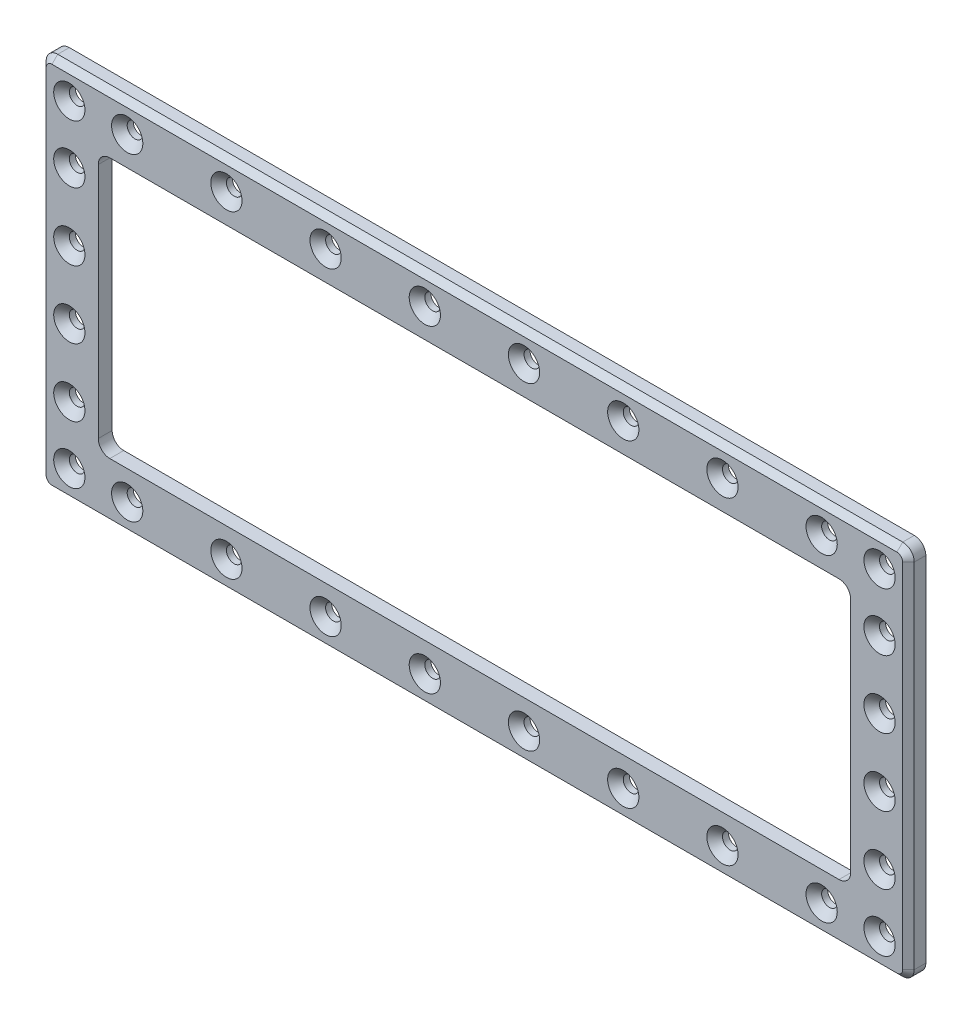
SolidWorks part; units mm, degrees
material "AISI Type 316L stainless steel"
ref_plane "Front Plane" through (0, 0, 0) normal (0, 0, 1) x (1, 0, 0)
ref_plane "Top Plane" through (0, 0, 0) normal (0, 1, 0) x (1, 0, 0)
ref_plane "Right Plane" through (0, 0, 0) normal (1, 0, 0) x (0, 0, -1)
sketch "Sketch1" plane through (0, 0, 0) normal (0, 0, 1) x (1, 0, 0)
  line L1 (75, -32.5) -> (-75, -32.5)
  line L2 (75, -32.5) -> (75, 32.5)
  line L3 (75, 32.5) -> (-75, 32.5)
  line L4 (-75, -32.5) -> (-75, 32.5)
  line L5 (75, -32.5) -> (-75, 32.5) construction
  line L6 (75, 32.5) -> (-75, -32.5) construction
  dimension "D1" = 150
  dimension "D2" = 65
extrude "Boss-Extrude1" add sketch "Sketch1" along normal blind 3
sketch "Sketch2" plane through (0, 0, 3) normal (0, 0, 1) x (1, 0, 0)
  line L1 (65, -22.5) -> (-65, -22.5)
  line L2 (65, -22.5) -> (65, 22.5)
  line L3 (65, 22.5) -> (-65, 22.5)
  line L4 (-65, -22.5) -> (-65, 22.5)
  line L5 (65, -22.5) -> (-65, 22.5) construction
  line L6 (65, 22.5) -> (-65, -22.5) construction
  point P0 (0, 0)
  dimension "D1" = 45
  dimension "D2" = 130
extrude "Cut-Extrude1" cut sketch "Sketch2" against normal through all
fillet "Fillet1" radius 2 8 edges at (75, 32.5, 1.5) (75, -32.5, 1.5) (-75, -32.5, 1.5) (-75, 32.5, 1.5) (65, 22.5, 1.5) (65, -22.5, 1.5) (-65, -22.5, 1.5) (-65, 22.5, 1.5)
sketch "Sketch3" plane through (0, 0, 0) normal (0, 0, 1) x (1, 0, 0)
  line L1 (72.5, -30) -> (-72.5, -30)
  line L2 (72.5, -30) -> (72.5, 30)
  line L3 (72.5, 30) -> (-72.5, 30)
  line L4 (-72.5, -30) -> (-72.5, 30)
  line L5 (72.5, -30) -> (-72.5, 30) construction
  line L6 (72.5, 30) -> (-72.5, -30) construction
  point P0 (0, 0)
  dimension "D1" = 60
  dimension "D2" = 145
extrude "Cut-Extrude2" cut sketch "Sketch3" along normal blind 0.6
fillet "Fillet2" radius 2 4 edges at (-72.5, -30, 0.3) (72.5, -30, 0.3) (72.5, 30, 0.3) (-72.5, 30, 0.3)
sketch "Sketch4" plane through (0, 0, 3) normal (0, 0, 1) x (1, 0, 0)
  line L0 (-75, 30.5) -> (-75, -30.5) construction
  line L1 (73, 32.5) -> (-73, 32.5) construction
  line L2 (0, -1.65) -> (0, 1.65) construction
  line L3 (1.65, 0) -> (-1.65, 0) construction
  point P0 (-70, 27.5)
  point P1 (-60, 27.5)
  point P2 (-70, 17.5)
  point P7 (-42.8571, 27.5)
  point P8 (-25.7143, 27.5)
  point P9 (70, -17.5)
  point P10 (-8.5714, 27.5)
  point P11 (8.5714, 27.5)
  point P12 (25.7143, 27.5)
  point P13 (42.8571, 27.5)
  point P14 (60, 27.5)
  point P17 (70, 27.5)
  point P18 (-70, 5.8333)
  point P19 (-70, -5.8333)
  point P22 (-70, -27.5)
  point P23 (-70, -17.5)
  point P24 (70, -5.8333)
  point P25 (70, 5.8333)
  point P26 (70, 17.5)
  point P27 (60, -27.5)
  point P28 (42.8571, -27.5)
  point P29 (25.7143, -27.5)
  point P30 (8.5714, -27.5)
  point P31 (-8.5714, -27.5)
  point P32 (-25.7143, -27.5)
  point P33 (-42.8571, -27.5)
  point P34 (-60, -27.5)
  point P37 (70, -27.5)
  dimension "D1" = 5
  dimension "D2" = 5
  dimension "D3" = 10
  dimension "D4" = 10
  dimension "D6" = 10
  dimension "D8" = 10
  dimension "D5" = 8
  dimension "D7" = 4
hole_wizard "CSK for M2.5 Cross recessed CTSK head wood screws1" positions "Sketch5" profile "Sketch7" countersink size "M2.5" standard "GB" end condition through all
sketch "Sketch5" plane through (0, 0, 3) normal (0, 0, 1) x (1, 0, 0)
  point P0 (-70, 27.5)
  point P3 (-70, 17.5)
  point P6 (-70, 5.8333)
  point P9 (-70, -5.8333)
  point P12 (-70, -17.5)
  point P15 (-70, -27.5)
  point P18 (-60, 27.5)
  point P21 (-42.8571, 27.5)
  point P24 (-25.7143, 27.5)
  point P27 (-8.5714, 27.5)
  point P30 (8.5714, 27.5)
  point P33 (25.7143, 27.5)
  point P36 (42.8571, 27.5)
  point P39 (60, 27.5)
  point P42 (70, 27.5)
  point P45 (70, 17.5)
  point P48 (70, 5.8333)
  point P51 (70, -5.8333)
  point P54 (70, -17.5)
  point P57 (70, -27.5)
  point P60 (60, -27.5)
  point P63 (42.8571, -27.5)
  point P66 (25.7143, -27.5)
  point P69 (8.5714, -27.5)
  point P72 (-8.5714, -27.5)
  point P75 (-25.7143, -27.5)
  point P78 (-42.8571, -27.5)
  point P81 (-60, -27.5)
sketch "Sketch7" plane through (-70, 27.5, 3) normal (1, 0, 0) x (0, -1, 0)
  line L0 (0, 0) -> (0, 3)
  line L1 (0, 3) -> (1.35, 3)
  line L2 (1.35, 3) -> (1.35, 1.35)
  line L3 (1.35, 1.35) -> (2.7, 0)
  line L5 (2.7, 0) -> (0, 0)
  line L6 (-1.35, 1.35) -> (-2.7, 0) construction
  line L11 (0, -6.35) -> (0, 107.95) construction
  dimension "Thru Hole Dia." = 2.7
  dimension "Thru Hole Depth" = 3
  dimension "Near C'Sink Dia." = 5.4
  dimension "Near C'Sink Angle" = 90
chamfer "Chamfer1" distance 1 angle 45 8 edges at (75, 0, 3) (74.4142, 31.9142, 3) (74.4142, -31.9142, 3) (0, 32.5, 3) (0, -32.5, 3) (-74.4142, 31.9142, 3) (-74.4142, -31.9142, 3) (-75, 0, 3)
